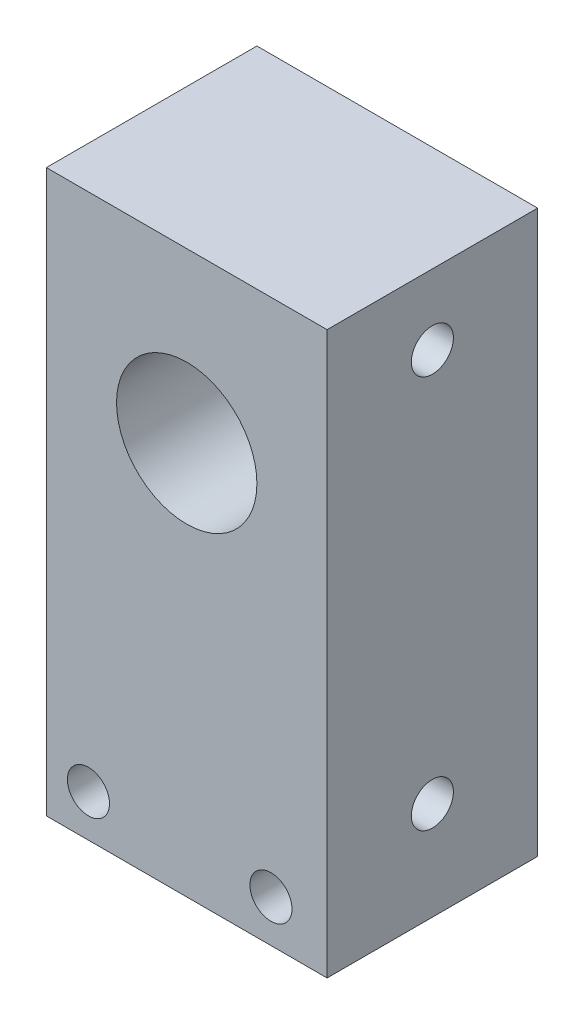
SolidWorks part; units mm, degrees
material "ABS"
ref_plane "Front" through (0, 0, 0) normal (0, 0, 1) x (1, 0, 0)
ref_plane "Top" through (0, 0, 0) normal (0, 1, 0) x (1, 0, 0)
ref_plane "Right" through (0, 0, 0) normal (1, 0, 0) x (0, 0, -1)
sketch "Esquisse1" plane through (0, 0, 0) normal (0, 0, 1) x (1, 0, 0)
  line L1 (0, 0) -> (20, 0)
  line L2 (0, 0) -> (0, 40)
  line L3 (0, 40) -> (20, 40)
  line L4 (20, 0) -> (20, 40)
  dimension "D1" = 20
  dimension "D2" = 40
extrude "Boss.-Extru.1" add sketch "Esquisse1" along normal blind 15
sketch "Esquisse2" plane through (20, 0, 0) normal (1, 0, 0) x (0, 0, -1)
  line L0 (0, 0) -> (0, 40) construction
  line L1 (-15, 40) -> (0, 40) construction
  circle A0 centre (-7.5, 35) radius 1.5
  circle A1 centre (-7.5, 7) radius 1.5
  dimension "D1" = 3
  dimension "D2" = 7.5
  dimension "D3" = 28
  dimension "D4" = 5
extrude "Enlèv. mat.-Extru.1" cut sketch "Esquisse2" against normal blind 10
sketch "Esquisse3" plane through (0, 0, 0) normal (0, 0, -1) x (-1, 0, 0)
  line L0 (0, 0) -> (-20, 0) construction
  line L1 (0, 40) -> (0, 0) construction
  circle A0 centre (-16, 3) radius 1.5
  circle A1 centre (-3, 3) radius 1.5
  dimension "D1" = 3
  dimension "D2" = 3
  dimension "D3" = 13
  dimension "D4" = 3
extrude "Enlèv. mat.-Extru.2" cut sketch "Esquisse3" against normal through all
sketch "Esquisse4" plane through (0, 0, 0) normal (0, 0, -1) x (-1, 0, 0)
  line L0 (-20, 40) -> (0, 40) construction
  line L1 (-20, 0) -> (-20, 40) construction
  circle A0 centre (-10, 28) radius 5
  dimension "D1" = 10
  dimension "D3" = 10
  dimension "D2" = 12
extrude "Enlèv. mat.-Extru.3" cut sketch "Esquisse4" against normal through all
